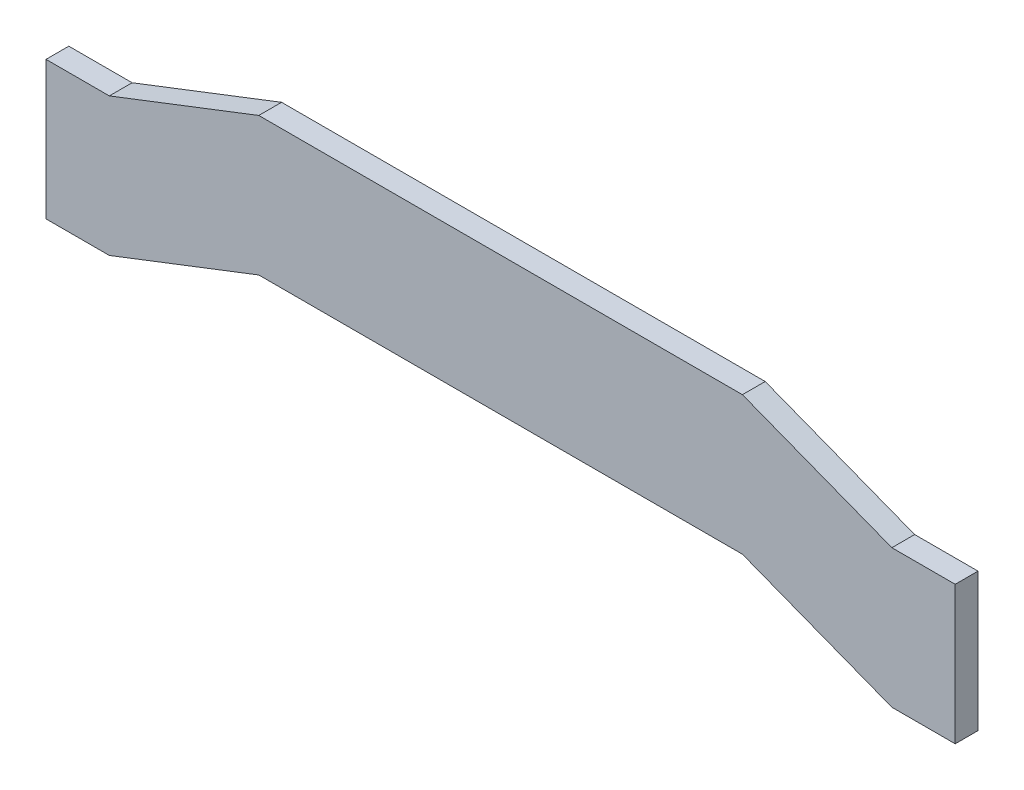
SolidWorks part; units mm, degrees
material "Pinho"
ref_plane "Plano frontal" through (0, 0, 0) normal (0, 0, 1) x (1, 0, 0)
ref_plane "Plano superior" through (0, 0, 0) normal (0, 1, 0) x (1, 0, 0)
ref_plane "Plano direito" through (0, 0, 0) normal (1, 0, 0) x (0, 0, -1)
sketch "Esboço1" plane through (0, 0, 0) normal (0, 0, 1) x (1, 0, 0)
  line L1 (-210, 70) -> (210, 70)
  line L3 (394.8, 19.8) -> (394.8, 139.8)
  line L5 (210, 190) -> (-210, 190)
  line L7 (-394.8, 139.8) -> (-394.8, 19.8)
  line L8 (0, 190) -> (0, 70) construction
  line L9 (0, 70) -> (0, 2.3109) construction
  line L10 (-210, 190) -> (-210, 70) construction
  line L11 (210, 190) -> (210, 70) construction
  line L12 (-394.8, 19.8) -> (394.8, 19.8) construction
  line L13 (-394.8, 19.8) -> (-339.8, 19.8)
  line L14 (-339.8, 19.8) -> (-210, 70)
  line L15 (-394.8, 139.8) -> (-339.8, 139.8)
  line L16 (-339.8, 139.8) -> (-210, 190)
  line L17 (-339.8, 139.8) -> (-339.8, 19.8) construction
  line L18 (394.8, 19.8) -> (339.8, 19.8)
  line L19 (339.8, 19.8) -> (210, 70)
  line L20 (394.8, 139.8) -> (339.8, 139.8)
  line L21 (339.8, 139.8) -> (210, 190)
  line L22 (339.8, 139.8) -> (339.8, 19.8) construction
  line L23 (-387.5771, 0) -> (387.5771, 0) construction
  line L24 (-339.8, 139.8) -> (339.8, 139.8) construction
  line L25 (0, 2.3109) -> (0, 0) construction
  point P18 (0, 0)
  dimension "D1" = 789.6
  dimension "D4" = 420
  dimension "D5" = 394.8
  dimension "D6" = 19.8
  dimension "D2" = 70
  dimension "D8" = 120
  dimension "D9" = 120
  dimension "D3" = 55
  dimension "D7" = 55
  dimension "D10" = 170.2
  dimension "D11" = 190
extrude "Ressalto-extrusão1" add sketch "Esboço1" along normal blind 19.8
equation "\"D5@Esboço1\"=\"D1@Esboço1\"/2"
